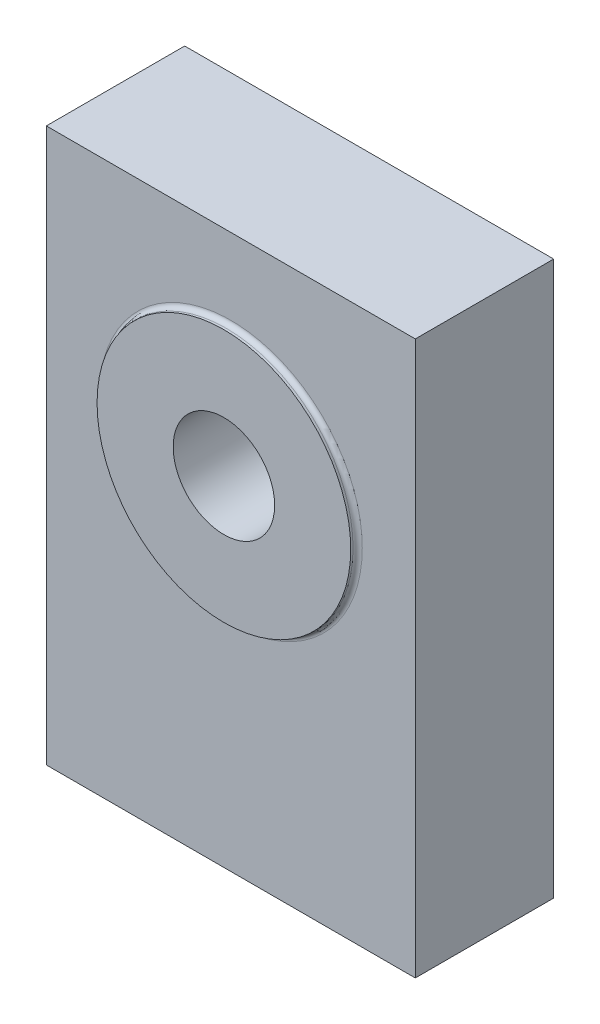
SolidWorks part; units mm, degrees
ref_plane "前视基准面" through (0, 0, 0) normal (0, 0, 1) x (1, 0, 0)
ref_plane "上视基准面" through (0, 0, 0) normal (0, 1, 0) x (1, 0, 0)
ref_plane "右视基准面" through (0, 0, 0) normal (1, 0, 0) x (0, 0, -1)
sketch "草图1" plane through (0, 0, 0) normal (0, 1, 0) x (1, 0, 0)
  line L1 (-40, -15) -> (40, -15)
  line L2 (-40, -15) -> (-40, 15)
  line L3 (-40, 15) -> (40, 15)
  line L4 (40, -15) -> (40, 15)
  line L5 (-40, -15) -> (40, 15) construction
  line L6 (-40, 15) -> (40, -15) construction
  point P0 (0, 0)
  dimension "D1" = 30
  dimension "D2" = 80
extrude "凸台-拉伸1" add sketch "草图1" along normal blind 120
sketch "草图2" plane through (0, 0, 15) normal (0, 0, 1) x (1, 0, 0)
  circle A0 centre (0, 75) radius 27.5
  dimension "D1" = 55
  dimension "D2" = 75
extrude "凸台-拉伸2" add sketch "草图2" along normal blind 1.5
sketch "草图3" plane through (0, 0, 16.5) normal (0, 0, 1) x (1, 0, 0)
  circle A0 centre (0, 75) radius 11
extrude "切除-拉伸1" cut sketch "草图3" against normal blind 39.5
fillet "圆角1" radius 1 1 edges at (-27.5, 75, 15)
